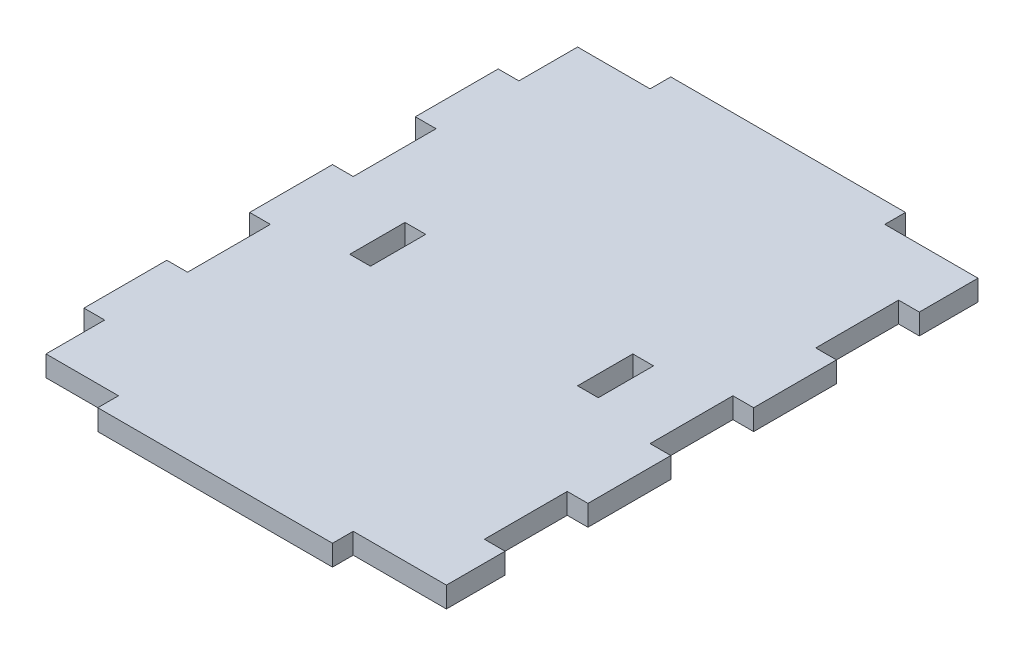
SolidWorks part; units mm, degrees
ref_plane "Alzado" through (0, 0, 0) normal (0, 0, 1) x (1, 0, 0)
ref_plane "Planta" through (0, 0, 0) normal (0, 1, 0) x (1, 0, 0)
ref_plane "Vista lateral" through (0, 0, 0) normal (1, 0, 0) x (0, 0, -1)
sketch "Croquis1" plane through (0, 0, 0) normal (0, 1, 0) x (1, 0, 0)
  line L0 (13.5, 0) -> (47.5, 0)
  line L1 (30.5, 0) -> (13.5, 0)
  line L2 (30.5, 0) -> (47.5, 0)
  line L3 (47.5, 0) -> (47.5, 3)
  line L4 (58, 35.5) -> (58, 47.5)
  line L5 (13.5, 3) -> (13.5, 0)
  line L6 (61, 3) -> (61, 11.5)
  line L7 (0, 11.5) -> (0, 23.5)
  line L8 (61, 23.5) -> (61, 35.5)
  line L9 (13.5, 80) -> (13.5, 83)
  line L10 (58, 47.5) -> (61, 47.5)
  line L11 (47.5, 83) -> (47.5, 80)
  line L12 (13.5, 83) -> (47.5, 83)
  line L13 (13.5, 80) -> (3, 80)
  line L14 (47.5, 80) -> (61, 80)
  line L15 (13.5, 3) -> (3, 3)
  line L16 (47.5, 3) -> (61, 3)
  line L17 (61, 47.5) -> (61, 59.5)
  line L18 (61, 59.5) -> (58, 59.5)
  line L19 (58, 59.5) -> (58, 71.5)
  line L20 (58, 71.5) -> (61, 71.5)
  line L21 (58, 11.5) -> (61, 11.5)
  line L22 (58, 23.5) -> (58, 11.5)
  line L23 (61, 23.5) -> (58, 23.5)
  line L24 (58, 35.5) -> (61, 35.5)
  line L26 (3, 35.5) -> (0, 35.5)
  line L27 (0, 23.5) -> (3, 23.5)
  line L29 (3, 11.5) -> (0, 11.5)
  line L30 (3, 71.5) -> (0, 71.5)
  line L31 (3, 11.5) -> (3, 3)
  line L32 (0, 59.5) -> (3, 59.5)
  line L33 (3, 47.5) -> (0, 47.5)
  line L36 (3, 80) -> (3, 71.5)
  line L37 (61, 71.5) -> (61, 80)
  line L38 (61, 47.5) -> (61, 59.5)
  line L39 (0, 59.5) -> (0, 71.5)
  line L40 (0, 35.5) -> (0, 47.5)
  line L41 (3, 59.5) -> (3, 47.5)
  line L42 (3, 35.5) -> (3, 23.5)
  dimension "D3" = 17
  dimension "D4" = 3
  dimension "D5" = 12
  dimension "D6" = 12
extrude "Saliente-Extruir1" add sketch "Croquis1" along normal blind 3 contours L26 L42 L27 L7 L29 L31 L15 L5 L0 L3 L16 L6 L21 L22 L23 L8 L24 L4 L10 L17 L18 L19 L20 L37 L14 L11 L12 L9 L13 L36 L30 L39 L32 L41 L33 L40
sketch "Croquis2" plane through (0, 3, 0) normal (0, 1, 0) x (1, 0, 0)
  line L0 (45.5, 41.5) -> (15.5, 41.5) construction
  line L1 (15.5, 41.5) -> (15.5, 45.5)
  line L2 (15.5, 45.5) -> (12.5, 45.5)
  line L3 (12.5, 45.5) -> (12.5, 37.5)
  line L4 (12.5, 37.5) -> (15.5, 37.5)
  line L5 (15.5, 37.5) -> (15.5, 41.5)
  line L6 (45.5, 37.5) -> (45.5, 41.5)
  line L7 (30.5, 83) -> (30.5, 0) construction
  line L8 (48.5, 37.5) -> (45.5, 37.5)
  line L9 (48.5, 45.5) -> (48.5, 37.5)
  line L10 (45.5, 45.5) -> (48.5, 45.5)
  line L11 (45.5, 41.5) -> (45.5, 45.5)
  line L13 (13.5, 83) -> (47.5, 83) construction
  line L15 (13.5, 0) -> (47.5, 0) construction
  point P17 (30.5, 41.5)
  dimension "D1" = 15
  dimension "D2" = 4
  dimension "D3" = 3
  dimension "D4" = 8
extrude "Cortar-Extruir1" cut sketch "Croquis2" against normal blind 10
